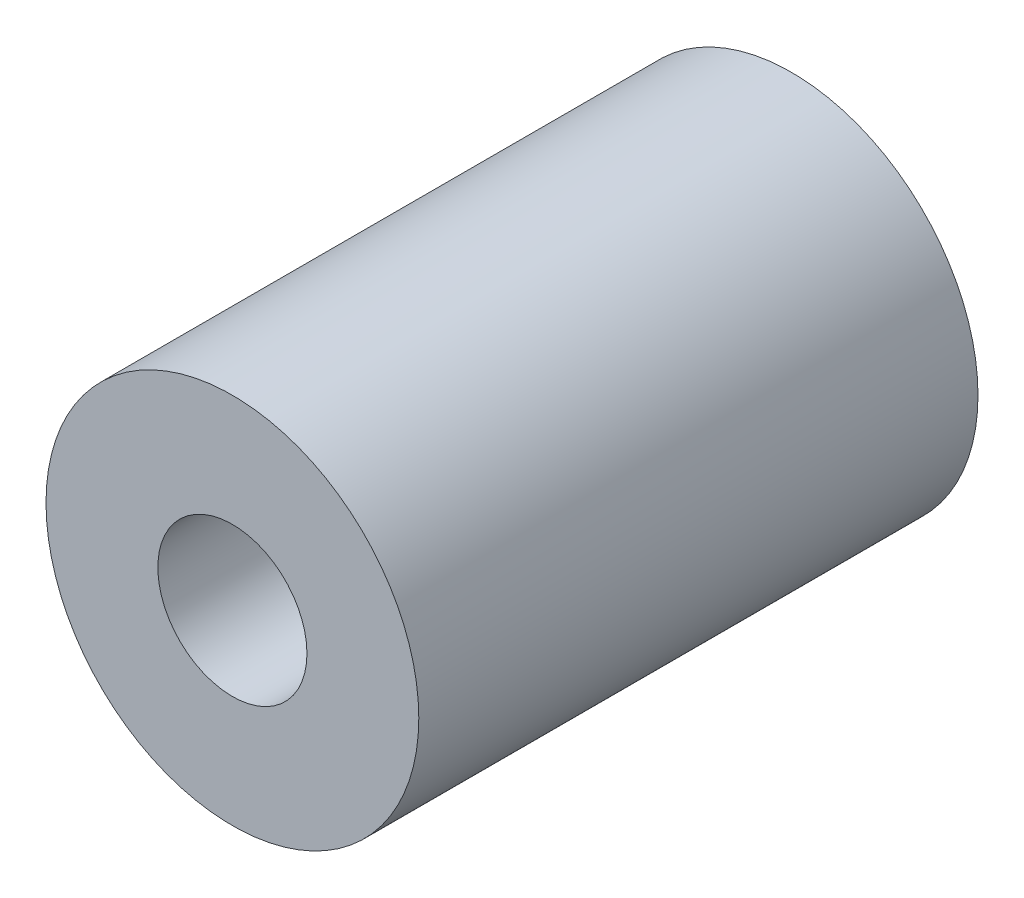
SolidWorks part; units mm, degrees
ref_plane "Front Plane" through (0, 0, 0) normal (0, 0, 1) x (1, 0, 0)
ref_plane "Top Plane" through (0, 0, 0) normal (0, 1, 0) x (1, 0, 0)
ref_plane "Right Plane" through (0, 0, 0) normal (1, 0, 0) x (0, 0, -1)
sketch "Sketch1" plane through (0, 0, 0) normal (0, 0, 1) x (1, 0, 0)
  circle A0 centre (0, 0) radius 0.0656
  circle A1 centre (0, 0) radius 10
  dimension "D1" = 20
extrude "Boss-Extrude1" add sketch "Sketch1" along normal blind 30
sketch "Sketch2" plane through (0, 0, 30) normal (0, 0, 1) x (1, 0, 0)
  circle A0 centre (0, 0) radius 4
  dimension "D1" = 8
extrude "Cut-Extrude1" cut sketch "Sketch2" against normal blind 30
sketch "Sketch3" plane through (0, 0, 0) normal (0, 0, -1) x (-1, 0, 0)
  circle A0 centre (0, 0) radius 5
  dimension "D1" = 10
extrude "Cut-Extrude2" cut sketch "Sketch3" against normal blind 15
